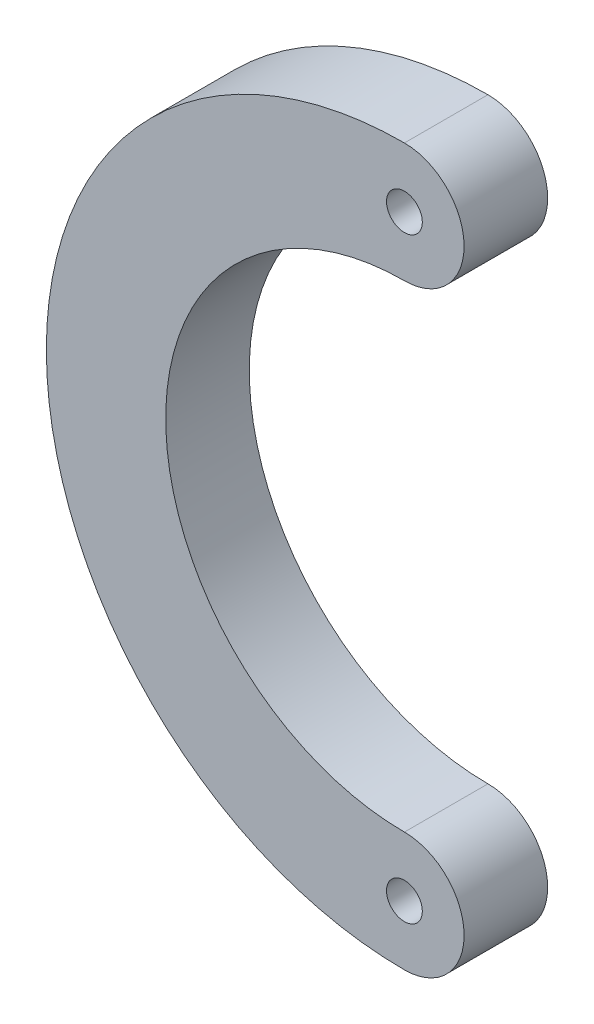
SolidWorks part; units mm, degrees
material "1060 Alloy"
ref_plane "Front Plane" through (0, 0, 0) normal (0, 0, 1) x (1, 0, 0)
ref_plane "Top Plane" through (0, 0, 0) normal (0, 1, 0) x (1, 0, 0)
ref_plane "Right Plane" through (0, 0, 0) normal (1, 0, 0) x (0, 0, -1)
sketch "Sketch1" plane through (0, 0, 0) normal (0, 0, 1) x (1, 0, 0)
  arc A0 (0, 30) -> (0, -30) centre (0, 0) ccw
  arc A1 (0, 20) -> (0, -20) centre (0, 0) ccw
  arc A2 (0, 20) -> (0, 30) centre (0, 25) ccw
  arc A3 (0, -30) -> (0, -20) centre (0, -25) ccw
  point P1 (0, -22.5)
  point P3 (0, 0)
  point P7 (0, 0)
  point P8 (0, 0)
  point P12 (0, 0)
  point P13 (0, 0)
  dimension "D1" = 10
  dimension "D3" = 5
  dimension "D4" = 5
  dimension "D2" = 50
extrude "Boss-Extrude1" add sketch "Sketch1" along normal blind 7
hole_wizard "Ø3.0mm Dowel Hole1" positions "Sketch2" profile "Sketch3" hole size "Ø3.0" standard "ANSI Metric" end condition through all
sketch "Sketch2" plane through (0, 0, 7) normal (0, 0, 1) x (1, 0, 0)
  arc A0 (0, -30) -> (0, -20) centre (0, -25) ccw construction
  arc A1 (0, 20) -> (0, 30) centre (0, 25) ccw construction
  point P0 (0, 25)
  point P2 (0, -25)
sketch "Sketch3" plane through (0, 25, 7) normal (1, 0, 0) x (0, -1, 0)
  line L0 (0, 0) -> (0, 7)
  line L1 (0, 7) -> (1.5, 7)
  line L2 (1.5, 7) -> (1.5, 0)
  line L5 (1.5, 0) -> (0, 0)
  line L11 (0, -6.35) -> (0, 107.95) construction
  dimension "Thru Hole Dia." = 3
  dimension "Thru Hole Depth" = 7
